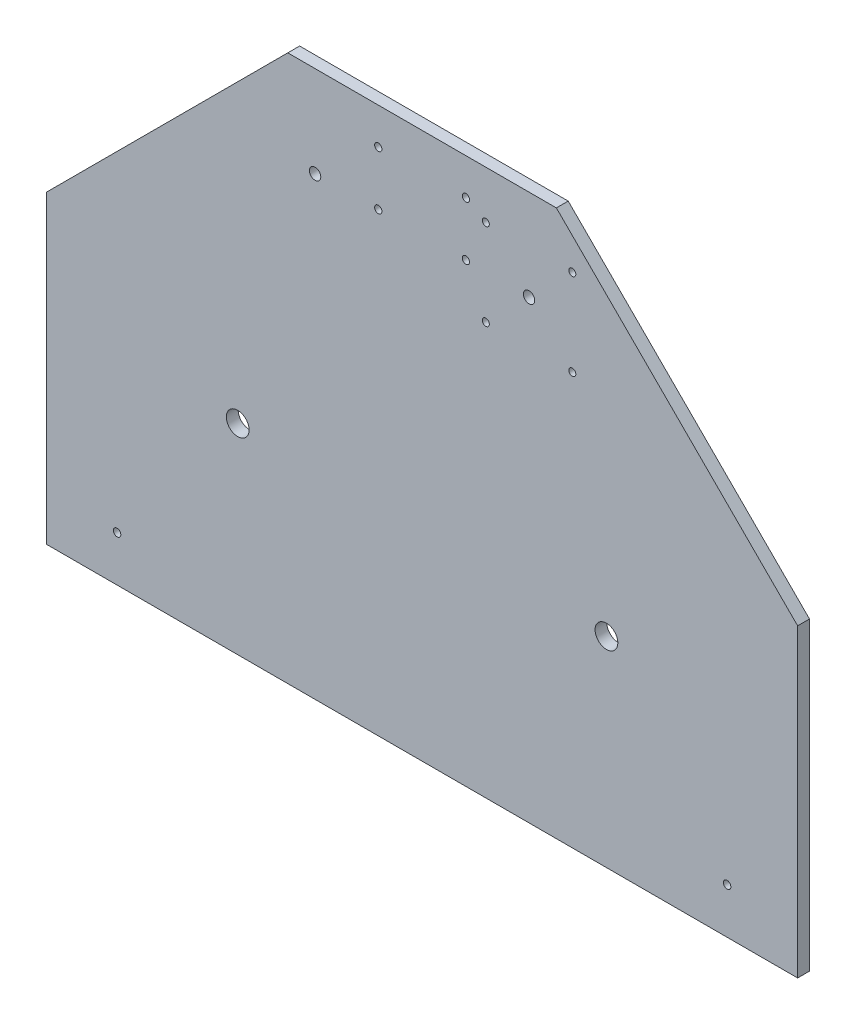
SolidWorks part; units mm, degrees
ref_plane "Front Plane" through (0, 0, 0) normal (0, 0, 1) x (1, 0, 0)
ref_plane "Top Plane" through (0, 0, 0) normal (0, 1, 0) x (1, 0, 0)
ref_plane "Right Plane" through (0, 0, 0) normal (1, 0, 0) x (0, 0, -1)
sketch "reference" plane through (0, 0, 0) normal (0, 0, 1) x (1, 0, 0)
  line L0 (209.55, 0) -> (-209.55, 0)
  line L1 (-209.55, 0) -> (-209.55, 170.18)
  line L2 (-209.55, 170.18) -> (-74.93, 304.8)
  line L3 (-74.93, 304.8) -> (74.93, 304.8)
  line L4 (0, 304.8) -> (0, 0) construction
  line L5 (209.55, 170.18) -> (74.93, 304.8)
  line L6 (209.55, 0) -> (209.55, 170.18)
  line L7 (-59.69, 276.2862) -> (59.69, 276.2862) construction
  line L8 (-31.75, 270.4499) -> (31.75, 270.4499) construction
  line L9 (31.75, 270.4499) -> (31.75, 262.8892) construction
  line L10 (31.75, 262.8892) -> (-31.75, 262.8892) construction
  line L11 (-31.75, 262.8892) -> (-31.75, 270.4499) construction
  line L12 (59.69, 254) -> (59.69, 229.87) construction
  line L13 (59.69, 229.87) -> (83.82, 229.87) construction
  line L14 (83.82, 229.87) -> (83.82, 254) construction
  line L15 (83.82, 254) -> (59.69, 254) construction
  circle A0 centre (-102.87, 111.76) radius 6.35
  circle A1 centre (-102.87, 111.76) radius 85.2442 construction
  circle A2 centre (-59.69, 254) radius 22.2862 construction
  circle A3 centre (59.69, 254) radius 22.2862 construction
  circle A4 centre (102.87, 111.76) radius 85.2442 construction
  circle A5 centre (102.87, 111.76) radius 6.35
  circle A6 centre (-59.69, 254) radius 3.175
  circle A7 centre (59.69, 254) radius 3.175
  circle A8 centre (170.18, 25.4) radius 2.0955
  circle A9 centre (-170.18, 25.4) radius 2.0955
  circle A10 centre (83.82, 229.87) radius 1.9685
  circle A11 centre (35.56, 229.87) radius 1.9685
  circle A12 centre (83.82, 278.13) radius 1.9685
  circle A13 centre (35.56, 278.13) radius 1.9685
  circle A14 centre (24.4475, 284.48) radius 2.032
  circle A15 centre (24.4475, 254.381) radius 2.032
  circle A16 centre (-24.4475, 254.381) radius 2.032
  circle A17 centre (-24.4475, 284.48) radius 2.032
  point P25 (0, 270.4499)
  dimension "D10" = 12.7
  dimension "D11" = 6.35
  dimension "D14" = 4.191
  dimension "D15" = 3.937
  dimension "D19" = 4.064
  dimension "D1" = 170.18
  dimension "D2" = 304.8
  dimension "D3" = 209.55
  dimension "D4" = 134.62
  dimension "D5" = 111.76
  dimension "D6" = 106.68
  dimension "D7" = 254
  dimension "D8" = 149.86
  dimension "D9" = 63.5
  dimension "D12" = 39.37
  dimension "D13" = 25.4
  dimension "D16" = 24.13
  dimension "D17" = 24.13
  dimension "D18" = 20.32
  dimension "D20" = 30.099
  dimension "D21" = 48.895
extrude "Boss-Extrude3" add sketch "reference" along normal blind 6.604
